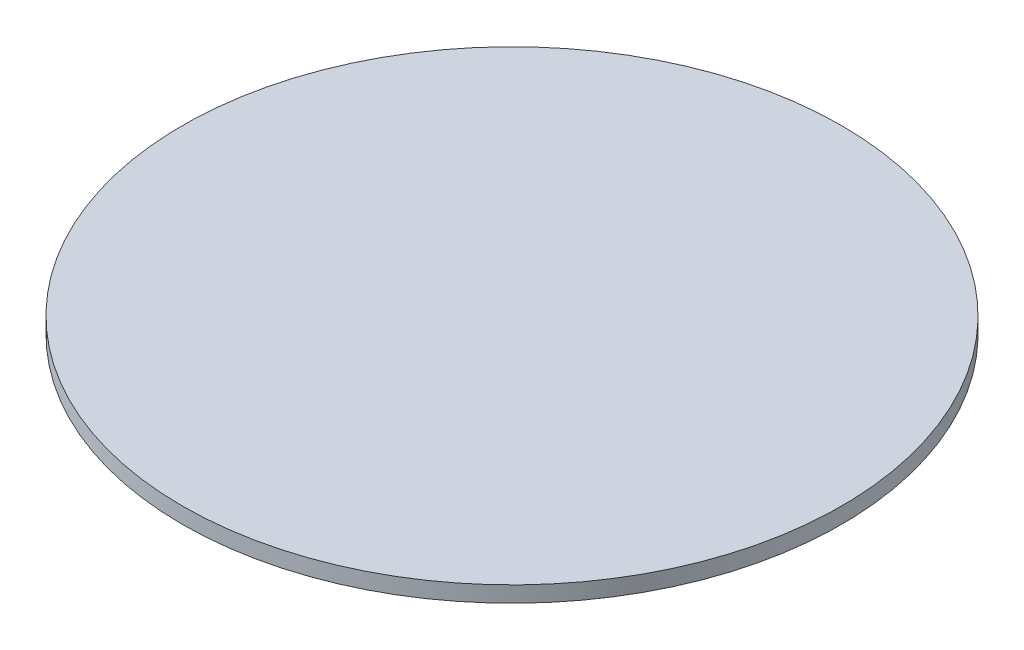
SolidWorks part; units mm, degrees
ref_plane "前视基准面" through (0, 0, 0) normal (0, 0, 1) x (1, 0, 0)
ref_plane "上视基准面" through (0, 0, 0) normal (0, 1, 0) x (1, 0, 0)
ref_plane "右视基准面" through (0, 0, 0) normal (1, 0, 0) x (0, 0, -1)
other "Configuration Table"
sketch "草图1" plane through (0, 0, 0) normal (0, 1, 0) x (1, 0, 0)
  circle A0 centre (0, 0) radius 62.09
extrude "凸台-拉伸1" add sketch "草图1" along normal blind 3
